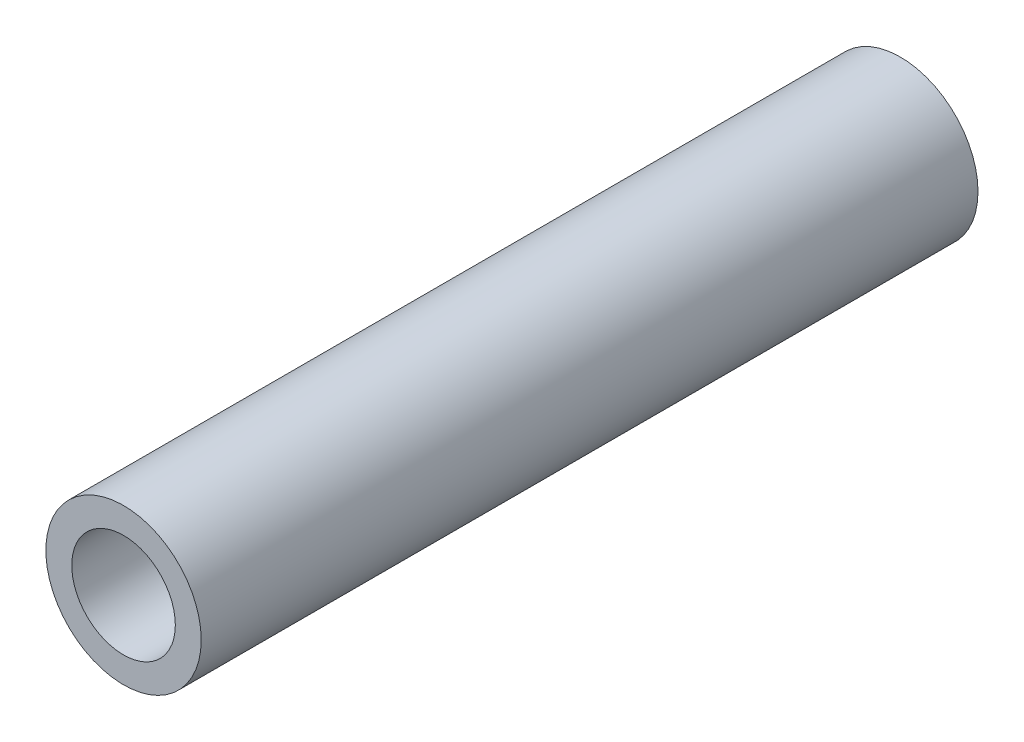
SolidWorks part; units mm, degrees
ref_plane "前视基准面" through (0, 0, 0) normal (0, 0, 1) x (1, 0, 0)
ref_plane "上视基准面" through (0, 0, 0) normal (0, 1, 0) x (1, 0, 0)
ref_plane "右视基准面" through (0, 0, 0) normal (1, 0, 0) x (0, 0, -1)
sketch "草图1" plane through (0, 0, 0) normal (0, 0, 1) x (1, 0, 0)
  circle A0 centre (0, 0) radius 3
  circle A1 centre (0, 0) radius 2
  dimension "D1" = 4
  dimension "D2" = 6
extrude "凸台-拉伸1" add sketch "草图1" along normal mid plane 30
